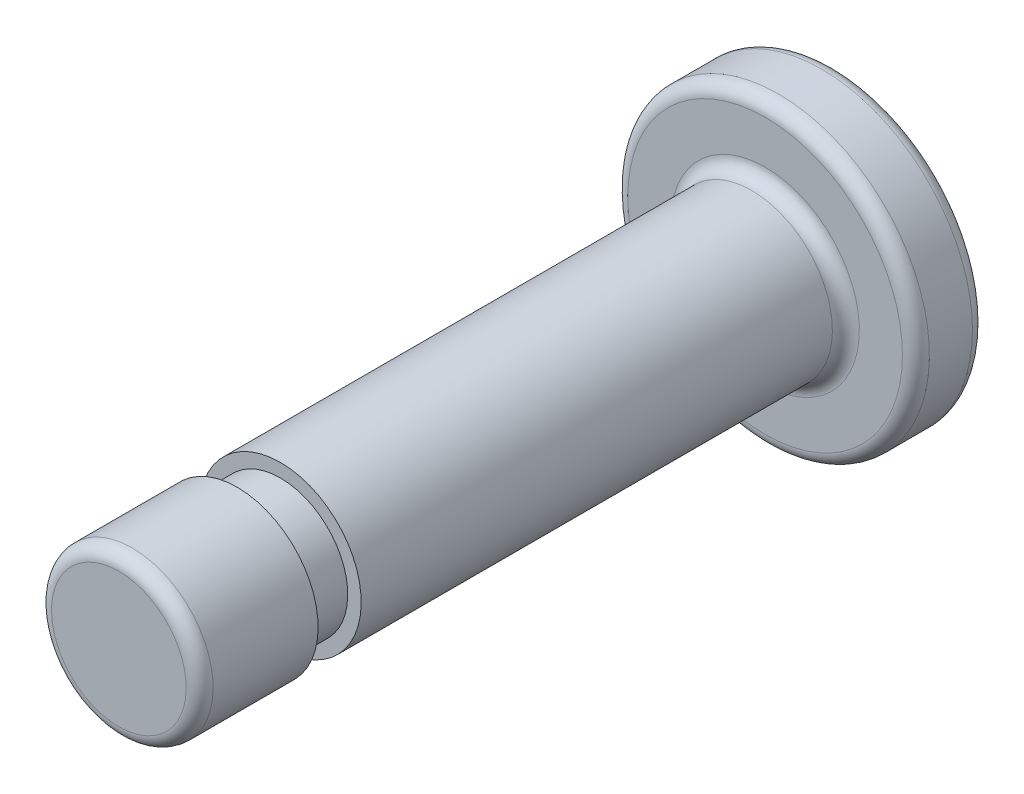
SolidWorks part; units mm, degrees
ref_plane "前视基准面" through (0, 0, 0) normal (1, 0, 0) x (0, 1, 0)
ref_plane "上视基准面" through (0, 0, 0) normal (0, 0, 1) x (0, 1, 0)
ref_plane "右视基准面" through (0, 0, 0) normal (0, 1, 0) x (-1, 0, 0)
other "Configuration Table"
sketch "草图1" plane through (0, 0, 0) normal (1, 0, 0) x (0, 1, 0)
  line L0 (0, 0) -> (-1.5, 0)
  line L1 (-1.5, 0) -> (-1.5, -2.2)
  line L2 (-1.5, -2.2) -> (-1.25, -2.2)
  line L3 (-1.25, -2.2) -> (-1.25, -3)
  line L4 (-1.25, -3) -> (-1.5, -3)
  line L5 (-1.5, -3) -> (-1.5, -12)
  line L6 (-1.5, -12) -> (-2.8, -12)
  line L7 (-2.8, -12) -> (-2.8, -13.3)
  line L8 (-2.8, -13.3) -> (0, -13.3)
  line L9 (0, -13.3) -> (0, 0)
  point P11 (-1.375, -3)
  dimension "D1" = 1.5
  dimension "D2" = 1.25
  dimension "D3" = 0.8
  dimension "D4" = 9
  dimension "D5" = 2.8
  dimension "D6" = 1.5
  dimension "D7" = 1.3
  dimension "D8" = 12
revolve "旋转1" add sketch "草图1" angle 360 about L9
fillet "圆角1" radius 0.25 4 edges at (0, 1.5, 0) (0, 2.8, -13.3) (0, 2.8, -12) (0, 1.5, -12)
